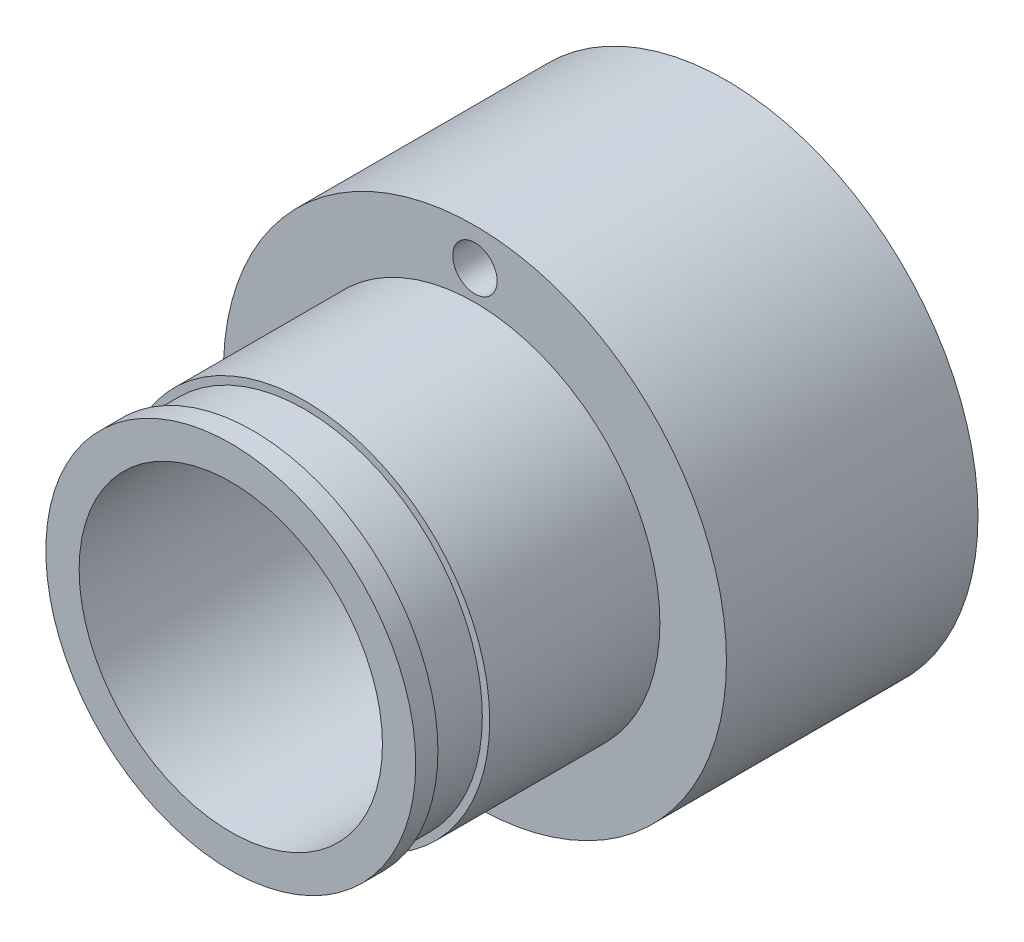
SolidWorks part; units mm, degrees
ref_plane "Plan de face" through (0, 0, 0) normal (0, 0, 1) x (1, 0, 0)
ref_plane "Plan de dessus" through (0, 0, 0) normal (0, 1, 0) x (1, 0, 0)
ref_plane "Plan de droite" through (0, 0, 0) normal (1, 0, 0) x (0, 0, -1)
sketch "Esquisse1" plane through (0, 0, 0) normal (0, 0, 1) x (1, 0, 0)
  circle A0 centre (0, 0) radius 17
  dimension "D1" = 34
extrude "Boss.-Extru.1" add sketch "Esquisse1" along normal blind 17
sketch "Esquisse2" plane through (0, 0, 17) normal (0, 0, 1) x (1, 0, 0)
  circle A0 centre (0, 0) radius 12.5
  dimension "D1" = 25
extrude "Boss.-Extru.2" add sketch "Esquisse2" along normal blind 11.5
sketch "Esquisse3" plane through (0, 0, 28.5) normal (0, 0, 1) x (1, 0, 0)
  circle A0 centre (0, 0) radius 12
  dimension "D1" = 24
extrude "Boss.-Extru.3" add sketch "Esquisse3" along normal blind 3.5
sketch "Esquisse4" plane through (0, 0, 32) normal (0, 0, 1) x (1, 0, 0)
  circle A0 centre (0, 0) radius 12.5
  dimension "D1" = 25
extrude "Boss.-Extru.4" add sketch "Esquisse4" along normal blind 1.5
sketch "Esquisse5" plane through (0, 0, 33.5) normal (0, 0, 1) x (1, 0, 0)
  circle A0 centre (0, 0) radius 10.25
  dimension "D1" = 20.5
extrude "Enlèv. mat.-Extru.1" cut sketch "Esquisse5" against normal blind 30
cosmetic thread "Représentation de filetage1" parameters "D1"=28, "D2"=21.5
sketch "Esquisse6" plane through (0, 0, 3.5) normal (0, 0, 1) x (1, 0, 0)
  circle A0 centre (0, 0) radius 10.25
  circle A1 centre (0, 0) radius 6.75
  dimension "D1" = 20.5
  dimension "D2" = 13.5
extrude "Enlèv. mat.-Extru.2" cut sketch "Esquisse6" against normal blind 1.5
sketch "Esquisse7" plane through (0, 0, 3.5) normal (0, 0, 1) x (1, 0, 0)
  circle A0 centre (0, 0) radius 12
  circle A1 centre (0, 0) radius 10.25
  dimension "D1" = 24
  dimension "D2" = 20.5
extrude "Enlèv. mat.-Extru.3" cut sketch "Esquisse7" along normal blind 2
hole_wizard "Diamètre du perçage Ø3.0 (3)1" positions "Esquisse9" profile "Esquisse8" hole size "Ø3.0" standard "ISO"
sketch "Esquisse9" plane through (0, 0, 17) normal (0, 0, 1) x (1, 0, 0)
  line L0 (0, 0) -> (0, 14.5) construction
  point P5 (0, 14.5)
  point P10 (0, 14.5)
  dimension "D1" = 14.5
sketch "Esquisse8" plane through (0, 14.5, 17) normal (1, 0, 0) x (0, -1, 0)
  line L0 (0, 0) -> (0, 12.9013)
  line L1 (0, 12.9013) -> (1.5, 12)
  line L2 (1.5, 12) -> (1.5, 0)
  line L5 (1.5, 0) -> (0, 0)
  line L10 (0, 12.9013) -> (-1.5, 12) construction
  line L11 (0, -6.35) -> (0, 107.95) construction
  dimension "Diamètre du perçage" = 3
  dimension "Profondeur du perçage" = 12
  dimension "Angle de pointe" = 118
